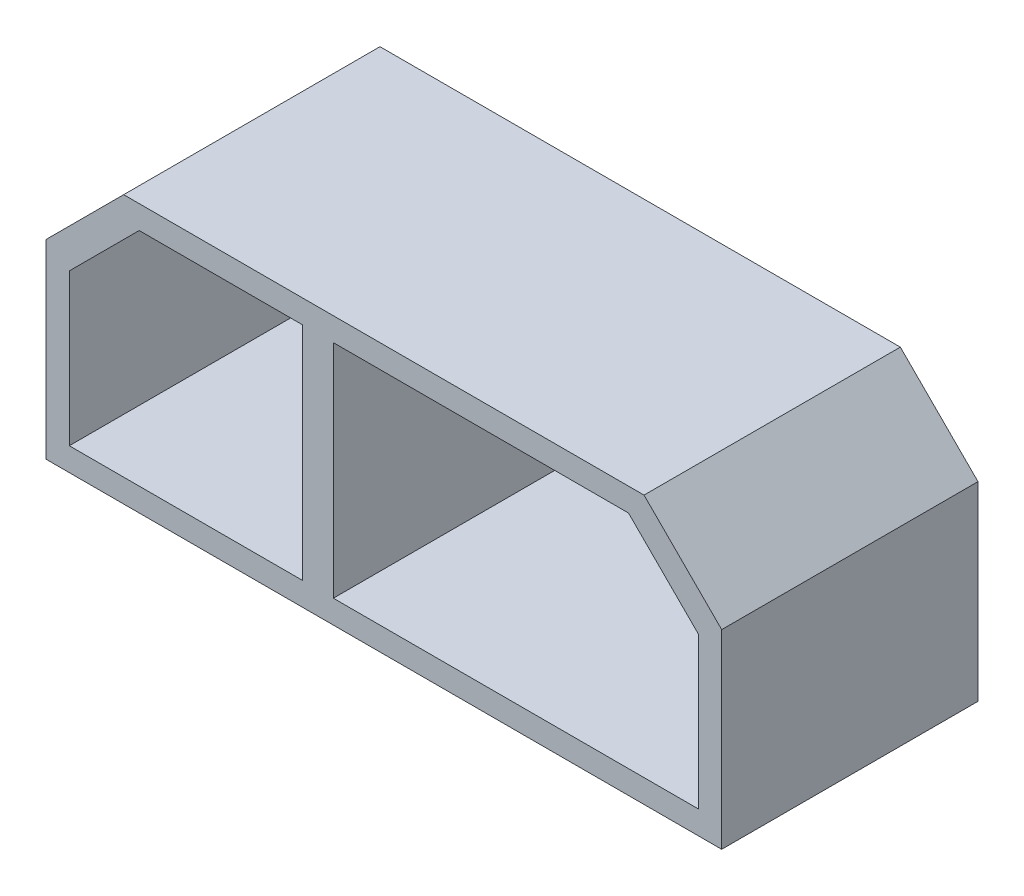
SolidWorks part; units mm, degrees
ref_plane "前视基准面" through (0, 0, 0) normal (0, 0, 1) x (1, 0, 0)
ref_plane "上视基准面" through (0, 0, 0) normal (0, 1, 0) x (1, 0, 0)
ref_plane "右视基准面" through (0, 0, 0) normal (1, 0, 0) x (0, 0, -1)
other "Configuration Table"
sketch "草图1" plane through (0, 0, 0) normal (0, 0, 1) x (1, 0, 0)
  line L1 (0, 0) -> (81, 0)
  line L2 (0, 0) -> (0, 28.5)
  line L3 (0, 28.5) -> (81, 28.5)
  line L4 (81, 0) -> (81, 28.5)
  dimension "D1" = 81
  dimension "D2" = 28.5
extrude "凸台-拉伸1" add sketch "草图1" along normal blind 3
sketch "草图2" plane through (0, 0, 3) normal (0, 0, 1) x (1, 0, 0)
  line L0 (81, 28.5) -> (0, 28.5) construction
  line L1 (84, -3) -> (-3, -3)
  line L2 (84, -3) -> (84, 31.5)
  line L3 (84, 31.5) -> (-3, 31.5)
  line L4 (-3, -3) -> (-3, 31.5)
  line L5 (84, -3) -> (-3, 31.5) construction
  line L6 (84, 31.5) -> (-3, -3) construction
  line L7 (0, 28.5) -> (0, 0) construction
  line L8 (0, 0) -> (81, 0) construction
  line L9 (81, 0) -> (81, 28.5) construction
  line L14 (0, 28.5) -> (0, 0)
  line L15 (0, 0) -> (81, 0)
  line L16 (81, 0) -> (81, 28.5)
  line L17 (81, 28.5) -> (0, 28.5)
  line L18 (0, 28.5) -> (0, 0)
  line L19 (0, 0) -> (81, 0)
  line L20 (81, 0) -> (81, 28.5)
  line L21 (81, 28.5) -> (0, 28.5)
  point P0 (40.5, 14.25)
  dimension "D1" = 3
  dimension "D2" = 3
  dimension "D3" = 3
  dimension "D4" = 3
  dimension "D5" = 0
extrude "凸台-拉伸2" add sketch "草图2" along normal blind 30 and the other way blind 3
sketch "草图3" plane through (0, 0, 3) normal (0, 0, 1) x (1, 0, 0)
  line L0 (81, 28.5) -> (0, 28.5) construction
  line L1 (30, 28.5) -> (34, 28.5)
  line L2 (30, 28.5) -> (30, 0)
  line L3 (30, 0) -> (34, 0)
  line L4 (34, 28.5) -> (34, 0)
  line L5 (0, 0) -> (81, 0) construction
  dimension "D1" = 4
extrude "凸台-拉伸3" add sketch "草图3" along normal blind 30
sketch "草图4" plane through (0, 0, 3) normal (0, 0, 1) x (1, 0, 0)
  line L0 (-3, 16.5) -> (12, 31.5)
  line L1 (-3, 31.5) -> (-3, -3) construction
  line L2 (84, 31.5) -> (-3, 31.5) construction
  line L3 (69, 31.5) -> (84, 16.5)
  line L4 (84, -3) -> (84, 31.5) construction
  line L5 (-3, 16.5) -> (-3, 31.5)
  line L6 (-3, 31.5) -> (12, 31.5)
  line L7 (69, 31.5) -> (84, 31.5)
  line L8 (84, 31.5) -> (84, 16.5)
  dimension "D1" = 15
  dimension "D2" = 15
  dimension "D3" = 15
  dimension "D4" = 15
extrude "凸台-拉伸4" add sketch "草图4" along normal blind 30
chamfer "倒角1" distance 10 angle 45 2 edges at (-3, 31.5, 16.5) (84, 31.5, 16.5)
